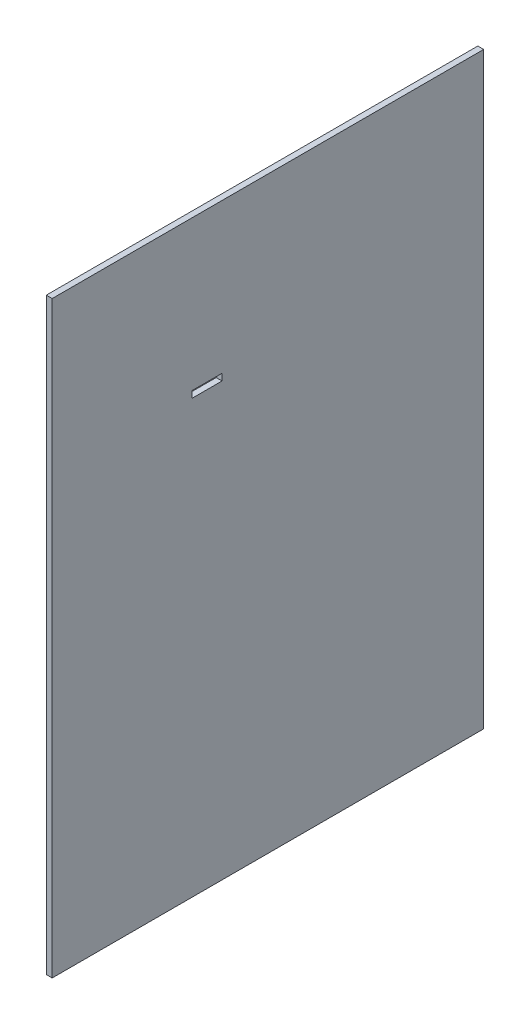
SolidWorks part; units mm, degrees
ref_plane "Front Plane" through (0, 0, 0) normal (0, 0, 1) x (1, 0, 0)
ref_plane "Top Plane" through (0, 0, 0) normal (0, 1, 0) x (1, 0, 0)
ref_plane "Right Plane" through (0, 0, 0) normal (1, 0, 0) x (0, 0, -1)
sketch "Sketch1" plane through (0, 0, 0) normal (1, 0, 0) x (0, 0, -1)
  line L1 (0, 0) -> (110, 0)
  line L2 (0, 0) -> (0, 150)
  line L3 (0, 150) -> (110, 150)
  line L4 (110, 0) -> (110, 150)
  line L12 (35.6061, 110.1512) -> (43.3061, 110.1512)
  line L13 (35.6061, 110.1512) -> (35.6061, 111.8504)
  line L14 (35.6061, 111.8504) -> (43.3061, 111.8504)
  line L15 (43.3061, 110.1512) -> (43.3061, 111.8504)
  line L16 (35.6061, 110.1512) -> (43.3061, 111.8504) construction
  line L17 (35.6061, 111.8504) -> (43.3061, 110.1512) construction
  circle A1 centre (39.4561, 87.1504) radius 23.8504 construction
  point P7 (39.4561, 111.0008)
  point P29 (39.3349, 107.7637)
  dimension "D1" = 1.6992
  dimension "D3" = 47.7008
  dimension "D2" = 7.7
  dimension "D4" = 150
  dimension "D5" = 110
extrude "Boss-Extrude1" add sketch "Sketch1" along normal blind 1.5
